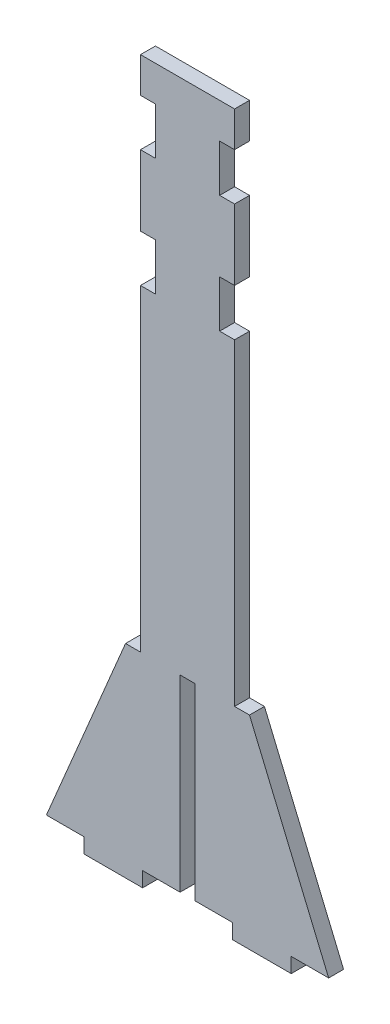
SolidWorks part; units mm, degrees
material "ABS"
ref_plane "Plan de face" through (0, 0, 0) normal (0, 0, 1) x (1, 0, 0)
ref_plane "Plan de dessus" through (0, 0, 0) normal (0, 1, 0) x (1, 0, 0)
ref_plane "Plan de droite" through (0, 0, 0) normal (1, 0, 0) x (0, 0, -1)
sketch "Esquisse1" plane through (0, 0, 0) normal (0, 0, 1) x (1, 0, 0)
  line L1 (-20, 300) -> (20, 300)
  line L2 (-20, 300) -> (-20, 80)
  line L4 (20, 300) -> (20, 80)
  line L8 (-60, 0) -> (60, 0)
  line L9 (26.35, 80) -> (-26.35, 80) construction
  line L10 (26.35, 80) -> (60, 0)
  line L11 (-26.35, 80) -> (-60, 0)
  line L12 (26.35, 80) -> (20, 80)
  line L13 (-20, 80) -> (-26.35, 80)
  point P1 (0, 0)
  point P2 (0, 300)
  point P8 (0, 80)
  dimension "D1" = 80
  dimension "D2" = 120
  dimension "D3" = 40
  dimension "D4" = 300
  dimension "D5" = 6.35
extrude "Boss.-Extru.1" add sketch "Esquisse1" along normal blind 6.35
sketch "Esquisse2" plane through (0, 0, 6.35) normal (0, 0, 1) x (1, 0, 0)
  line L0 (-60, 0) -> (60, 0) construction
  line L1 (-3.175, 80) -> (3.175, 80)
  line L2 (-3.175, 80) -> (-3.175, 0)
  line L3 (-3.175, 0) -> (3.175, 0)
  line L4 (3.175, 80) -> (3.175, 0)
  dimension "D1" = 6.35
extrude "Enlèv. mat.-Extru.1" cut sketch "Esquisse2" against normal up to next
sketch "Esquisse4" plane through (0, 0, 6.35) normal (0, 0, 1) x (1, 0, 0)
  line L0 (13.65, 235) -> (20, 235) construction
  line L1 (13.65, 215) -> (13.65, 235) construction
  line L2 (13.65, 215) -> (20, 215) construction
  line L3 (-20, 215) -> (-13.65, 215) construction
  line L4 (-13.65, 215) -> (-13.65, 235) construction
  line L5 (-20, 235) -> (-13.65, 235) construction
  line L6 (-20, 265) -> (-13.65, 265) construction
  line L7 (-13.65, 265) -> (-13.65, 285) construction
  line L8 (-20, 285) -> (-13.65, 285) construction
  line L9 (13.65, 265) -> (20, 265) construction
  line L10 (13.65, 265) -> (13.65, 285) construction
  line L11 (13.65, 285) -> (20, 285) construction
  line L12 (13.65, 235) -> (20, 235)
  line L13 (13.65, 215) -> (13.65, 235)
  line L14 (13.65, 215) -> (20, 215)
  line L15 (-20, 215) -> (-13.65, 215)
  line L16 (-13.65, 215) -> (-13.65, 235)
  line L17 (-20, 235) -> (-13.65, 235)
  line L18 (-20, 265) -> (-13.65, 265)
  line L19 (-13.65, 265) -> (-13.65, 285)
  line L20 (-20, 285) -> (-13.65, 285)
  line L21 (13.65, 265) -> (20, 265)
  line L22 (13.65, 265) -> (13.65, 285)
  line L23 (13.65, 285) -> (20, 285)
  line L24 (-20, 285) -> (-20, 265)
  line L25 (20, 285) -> (20, 265)
  line L26 (20, 235) -> (20, 215)
  line L27 (-20, 235) -> (-20, 215)
extrude "Enlèv. mat.-Extru.2" cut sketch "Esquisse4" against normal up to next
fillet "Congé1" [suppressed] radius 10
sketch "Sketch2" plane through (0, 0, 0) normal (0, -1, 0) x (-1, 0, 0)
  line L0 (60, -6.35) -> (3.175, -6.35) construction
  line L1 (19.0875, -6.35) -> (44.0875, -6.35)
  line L2 (19.0875, -6.35) -> (19.0875, 0)
  line L3 (19.0875, 0) -> (44.0875, 0)
  line L4 (44.0875, -6.35) -> (44.0875, 0)
  line L5 (60, 0) -> (3.175, 0) construction
  line L6 (0, 3.4925) -> (0, -3.4925) construction
  line L7 (-19.0875, -6.35) -> (-19.0875, 0)
  line L8 (-19.0875, 0) -> (-44.0875, 0)
  line L9 (-44.0875, -6.35) -> (-44.0875, 0)
  line L10 (-19.0875, -6.35) -> (-44.0875, -6.35)
  point P8 (31.5875, -6.35)
  point P9 (31.5875, -6.35)
  dimension "D1" = 25
extrude "Boss-Extrude2" add sketch "Sketch2" along normal blind 6.35
